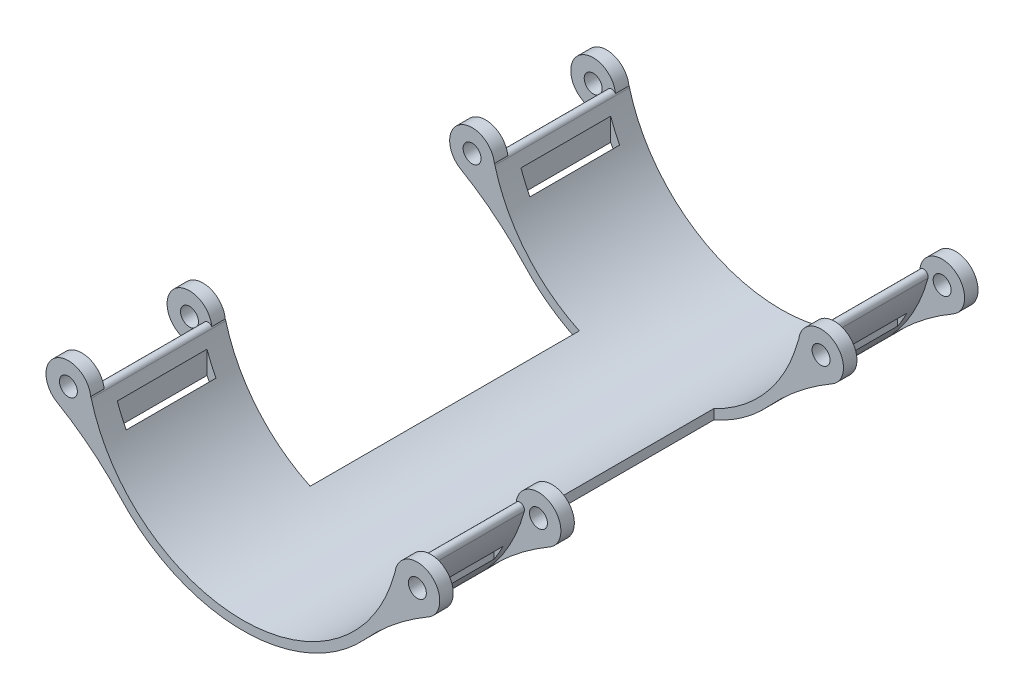
SolidWorks part; units mm, degrees
ref_plane "Front Plane" through (0, 0, 0) normal (0, 0, 1) x (1, 0, 0)
ref_plane "Top Plane" through (0, 0, 0) normal (0, 1, 0) x (1, 0, 0)
ref_plane "Right Plane" through (0, 0, 0) normal (1, 0, 0) x (0, 0, -1)
sketch "Sketch1" plane through (0, 0, 0) normal (0, 0, 1) x (1, 0, 0)
  line L0 (0, 0) -> (-33.8074, -9.0587) construction
  line L1 (33.8074, -9.0587) -> (0, 0) construction
  line L4 (-33.8074, -9.0587) -> (33.8074, -9.0587) construction
  arc A0 (33.8074, -9.0587) -> (-33.8074, -9.0587) centre (0, 0) cw
  arc A1 (35.7393, -9.5763) -> (-35.7393, -9.5763) centre (0, 0) cw
  arc A2 (33.8074, -9.0587) -> (35.7393, -9.5763) centre (34.7733, -9.3175) cw
  arc A3 (-33.8074, -9.0587) -> (-35.7393, -9.5763) centre (-34.7733, -9.3175) ccw
  dimension "D1" = 35
  dimension "D2" = 150
  dimension "D3" = 2
extrude "Boss-Extrude1" add sketch "Sketch1" along normal blind 120
sketch "Sketch2" plane through (0, 0, 0) normal (0, 1, 0) x (1, 0, 0)
  line L0 (0, 0) -> (0, -146.1851) construction
  line L1 (33.8074, -120) -> (33.8074, 0) construction
  line L2 (-55.1095, -30) -> (-15, -30)
  line L3 (-55.1095, -30) -> (-55.1095, -90)
  line L4 (-55.1095, -90) -> (-15, -90)
  line L5 (-15, -30) -> (-15, -90)
  line L6 (55.1095, -30) -> (15, -30)
  line L7 (55.1095, -30) -> (55.1095, -90)
  line L8 (55.1095, -90) -> (15, -90)
  line L9 (15, -30) -> (15, -90)
  line L10 (33.8074, -120) -> (33.8074, 0) construction
  line L12 (31, -5) -> (33, -5)
  line L13 (31, -5) -> (31, -25)
  line L14 (31, -25) -> (33, -25)
  line L15 (33, -5) -> (33, -25)
  line L20 (-31, -25) -> (-33, -25)
  line L21 (-33, -5) -> (-33, -25)
  line L22 (-31, -5) -> (-33, -5)
  line L23 (-31, -5) -> (-31, -25)
  line L24 (15, -60) -> (-94.2442, -60) construction
  line L25 (-31, -115) -> (-31, -95)
  line L26 (-31, -115) -> (-33, -115)
  line L27 (-33, -115) -> (-33, -95)
  line L28 (-31, -95) -> (-33, -95)
  line L29 (31, -95) -> (33, -95)
  line L30 (33, -115) -> (33, -95)
  line L31 (31, -115) -> (33, -115)
  line L32 (31, -115) -> (31, -95)
  point P13 (33.8074, -60)
  point P14 (15, -60)
  dimension "D1" = 30
  dimension "D2" = 60
  dimension "D3" = 20
  dimension "D4" = 5
  dimension "D5" = 33
  dimension "D6" = 2
extrude "Cut-Extrude1" cut sketch "Sketch2" against normal blind 120
sketch "Sketch3" plane through (0, 0, 0) normal (0, 0, -1) x (-1, 0, 0)
  line L0 (0, 0) -> (0, 24.5047) construction
  circle A0 centre (-38.8997, -9.3175) radius 2
  arc A2 (-33.8074, -9.0587) -> (33.8074, -9.0587) centre (0, 0) ccw construction
  circle A3 centre (-38.8997, -9.3175) radius 5
  circle A5 centre (-34.7733, -9.3175) radius 0.5155 construction
  circle A6 centre (38.8997, -9.3175) radius 2
  circle A7 centre (38.8997, -9.3175) radius 5
  point P2 (0, 0)
  dimension "D1" = 4
  dimension "D2" = 3
extrude "Boss-Extrude2" add sketch "Sketch3" against normal blind 3
sketch "Sketch4" plane through (0, 0, 30) normal (0, 0, 1) x (1, 0, 0)
  circle A0 centre (-38.8997, -9.3175) radius 2 construction
  circle A1 centre (-38.8997, -9.3175) radius 2
  circle A2 centre (38.8997, -9.3175) radius 2 construction
  circle A3 centre (38.8997, -9.3175) radius 2
  circle A4 centre (-38.8997, -9.3175) radius 5
  circle A5 centre (38.8997, -9.3175) radius 5
extrude "Boss-Extrude3" add sketch "Sketch4" against normal blind 3
pattern_linear "LPattern1" count 2 spacing 90 along (0, 0, 1) of "Boss-Extrude3", "Boss-Extrude2"
fillet "Fillet1" radius 60 8 edges at (-34.8928, -12.3083, 28.5) (-34.8928, -12.3083, 1.5) (34.8928, -12.3083, 1.5) (34.8928, -12.3083, 28.5) (34.8928, -12.3083, 91.5) (34.8928, -12.3083, 118.5) (-34.8928, -12.3083, 91.5) (-34.8928, -12.3083, 118.5)
